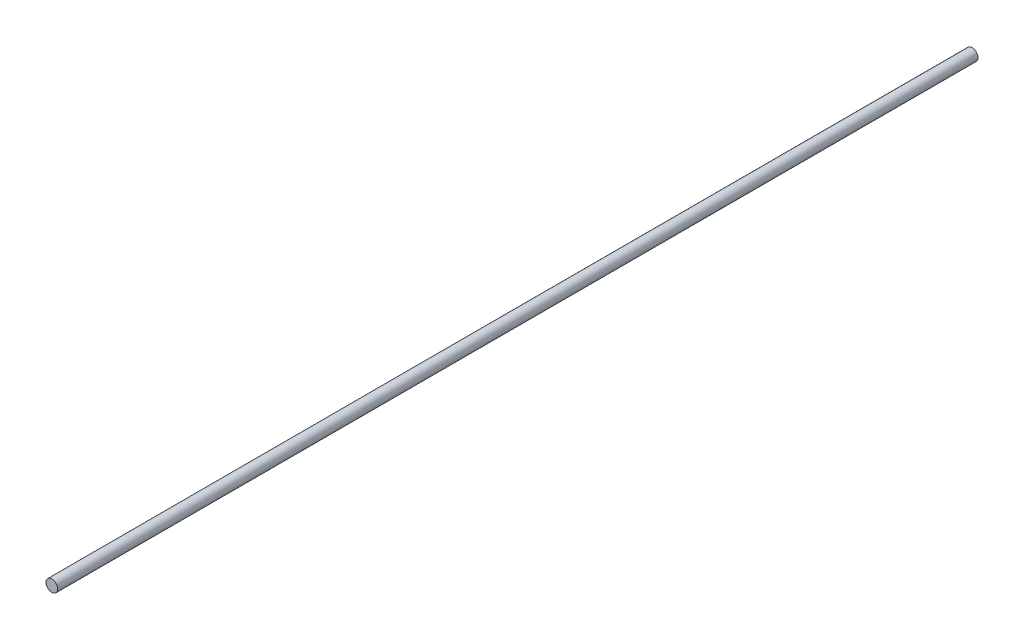
SolidWorks part; units mm, degrees
ref_plane "Front Plane" through (0, 0, 0) normal (0, 0, 1) x (1, 0, 0)
ref_plane "Top Plane" through (0, 0, 0) normal (0, 1, 0) x (1, 0, 0)
ref_plane "Right Plane" through (0, 0, 0) normal (1, 0, 0) x (0, 0, -1)
sketch "Sketch1" plane through (0, 0, 0) normal (0, 0, 1) x (1, 0, 0)
  circle A0 centre (0, 0) radius 3.175
  dimension "D1" = 6.35
extrude "Boss-Extrude1" add sketch "Sketch1" along normal blind 500
